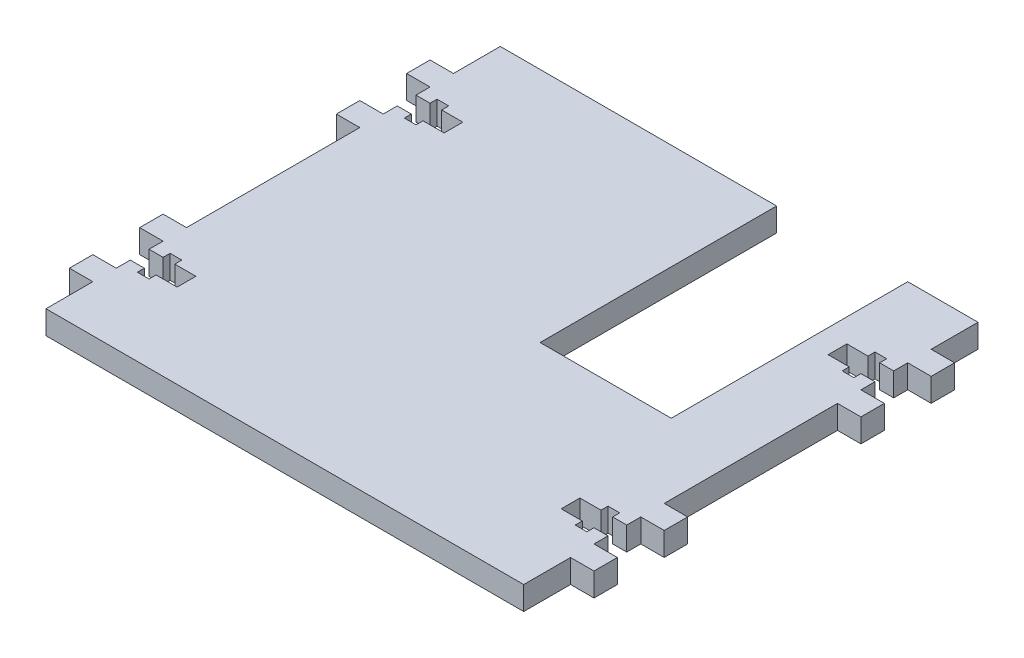
SolidWorks part; units mm, degrees
ref_plane "Front Plane" through (0, 0, 0) normal (0, 0, 1) x (1, 0, 0)
ref_plane "Top Plane" through (0, 0, 0) normal (0, 1, 0) x (1, 0, 0)
ref_plane "Right Plane" through (0, 0, 0) normal (1, 0, 0) x (0, 0, -1)
sketch "Sketch2" plane through (0, 0, 0) normal (0, 1, 0) x (1, 0, 0)
  line L58 (143.4819, 36.3281) -> (143.4819, 33.3281)
  line L59 (41.4819, 51.3281) -> (100.4819, 51.3281)
  line L84 (41.4819, 51.3281) -> (41.4819, 41.3281)
  line L85 (41.4819, -45.6719) -> (143.4819, -45.6719)
  line L86 (143.4819, 51.3281) -> (143.4819, 41.3281)
  line L87 (143.4819, 36.3281) -> (148.4819, 36.3281)
  line L88 (143.4819, 41.3281) -> (148.4819, 41.3281)
  line L89 (148.4819, 36.3281) -> (148.4819, 41.3281)
  line L90 (143.4819, 26.3281) -> (148.4819, 26.3281)
  line L91 (143.4819, 21.3281) -> (148.4819, 21.3281)
  line L92 (148.4819, 26.3281) -> (148.4819, 21.3281)
  line L93 (143.4819, 21.3281) -> (143.4819, -15.6719)
  line L94 (92.4819, 51.3281) -> (92.4819, -45.6719) construction
  line L95 (41.4819, 2.8281) -> (143.4819, 2.8281) construction
  line L96 (41.4819, 21.3281) -> (36.4819, 21.3281)
  line L97 (36.4819, 26.3281) -> (36.4819, 21.3281)
  line L98 (41.4819, 26.3281) -> (36.4819, 26.3281)
  line L99 (36.4819, 36.3281) -> (36.4819, 41.3281)
  line L100 (41.4819, 36.3281) -> (36.4819, 36.3281)
  line L101 (41.4819, 41.3281) -> (36.4819, 41.3281)
  line L102 (148.4819, -30.6719) -> (148.4819, -35.6719)
  line L103 (143.4819, -35.6719) -> (148.4819, -35.6719)
  line L104 (143.4819, -30.6719) -> (148.4819, -30.6719)
  line L105 (148.4819, -20.6719) -> (148.4819, -15.6719)
  line L106 (143.4819, -15.6719) -> (148.4819, -15.6719)
  line L107 (143.4819, -20.6719) -> (148.4819, -20.6719)
  line L108 (41.4819, -35.6719) -> (36.4819, -35.6719)
  line L109 (41.4819, -30.6719) -> (36.4819, -30.6719)
  line L110 (41.4819, -15.6719) -> (36.4819, -15.6719)
  line L111 (41.4819, -20.6719) -> (36.4819, -20.6719)
  line L112 (36.4819, -30.6719) -> (36.4819, -35.6719)
  line L113 (36.4819, -20.6719) -> (36.4819, -15.6719)
  line L114 (143.4819, -20.6719) -> (143.4819, -23.6719)
  line L115 (143.4819, -35.6719) -> (143.4819, -45.6719)
  line L116 (41.4819, -35.6719) -> (41.4819, -45.6719)
  line L117 (41.4819, -20.6719) -> (41.4819, -23.6719)
  line L118 (41.4819, 21.3281) -> (41.4819, -15.6719)
  line L119 (41.4819, 36.3281) -> (41.4819, 33.3281)
  line L120 (143.4819, 31.3281) -> (41.4819, 31.3281) construction
  line L121 (143.4819, 33.3281) -> (140.4819, 33.3281)
  line L122 (143.4819, 29.3281) -> (140.4819, 29.3281)
  line L123 (133.4819, 33.3281) -> (133.4819, 29.3281)
  line L124 (140.4819, 33.3281) -> (140.4819, 34.8281)
  line L125 (140.4819, 34.8281) -> (137.9819, 34.8281)
  line L126 (137.9819, 33.3281) -> (137.9819, 34.8281)
  line L127 (137.9819, 33.3281) -> (133.4819, 33.3281)
  line L128 (140.4819, 29.3281) -> (140.4819, 27.8281)
  line L129 (140.4819, 27.8281) -> (137.9819, 27.8281)
  line L130 (137.9819, 29.3281) -> (137.9819, 27.8281)
  line L131 (137.9819, 29.3281) -> (133.4819, 29.3281)
  line L132 (143.4819, 29.3281) -> (143.4819, 26.3281)
  line L133 (44.4819, 33.3281) -> (44.4819, 34.8281)
  line L134 (46.9819, 33.3281) -> (46.9819, 34.8281)
  line L135 (44.4819, 34.8281) -> (46.9819, 34.8281)
  line L136 (41.4819, 33.3281) -> (44.4819, 33.3281)
  line L137 (41.4819, 29.3281) -> (44.4819, 29.3281)
  line L138 (44.4819, 29.3281) -> (44.4819, 27.8281)
  line L139 (46.9819, 29.3281) -> (46.9819, 27.8281)
  line L140 (44.4819, 27.8281) -> (46.9819, 27.8281)
  line L141 (46.9819, 29.3281) -> (51.4819, 29.3281)
  line L142 (51.4819, 33.3281) -> (51.4819, 29.3281)
  line L143 (46.9819, 33.3281) -> (51.4819, 33.3281)
  line L144 (41.4819, -27.6719) -> (44.4819, -27.6719)
  line L145 (44.4819, -27.6719) -> (44.4819, -29.1719)
  line L146 (46.9819, -27.6719) -> (46.9819, -29.1719)
  line L147 (44.4819, -29.1719) -> (46.9819, -29.1719)
  line L148 (46.9819, -27.6719) -> (51.4819, -27.6719)
  line L149 (51.4819, -27.6719) -> (51.4819, -23.6719)
  line L150 (46.9819, -23.6719) -> (51.4819, -23.6719)
  line L151 (46.9819, -23.6719) -> (46.9819, -22.1719)
  line L152 (44.4819, -23.6719) -> (44.4819, -22.1719)
  line L153 (44.4819, -22.1719) -> (46.9819, -22.1719)
  line L154 (41.4819, -23.6719) -> (44.4819, -23.6719)
  line L155 (137.9819, -27.6719) -> (137.9819, -29.1719)
  line L156 (140.4819, -29.1719) -> (137.9819, -29.1719)
  line L157 (140.4819, -27.6719) -> (140.4819, -29.1719)
  line L158 (143.4819, -27.6719) -> (140.4819, -27.6719)
  line L159 (143.4819, -23.6719) -> (140.4819, -23.6719)
  line L160 (140.4819, -23.6719) -> (140.4819, -22.1719)
  line L161 (140.4819, -22.1719) -> (137.9819, -22.1719)
  line L162 (137.9819, -23.6719) -> (137.9819, -22.1719)
  line L163 (137.9819, -23.6719) -> (133.4819, -23.6719)
  line L164 (133.4819, -27.6719) -> (133.4819, -23.6719)
  line L165 (137.9819, -27.6719) -> (133.4819, -27.6719)
  line L166 (41.4819, 29.3281) -> (41.4819, 26.3281)
  line L167 (41.4819, -27.6719) -> (41.4819, -30.6719)
  line L168 (143.4819, -27.6719) -> (143.4819, -30.6719)
  line L169 (128.4819, 51.3281) -> (143.4819, 51.3281)
  line L171 (100.4819, 51.3281) -> (100.4819, 0.8281)
  line L172 (100.4819, 0.8281) -> (128.4819, 0.8281)
  line L173 (128.4819, 51.3281) -> (128.4819, 0.8281)
  dimension "D1" = 102
  dimension "D2" = 97
  dimension "D3" = 5
  dimension "D4" = 10
  dimension "D5" = 10
  dimension "D6" = 3
  dimension "D7" = 10
  dimension "D8" = 3
  dimension "D9" = 2.5
  dimension "D10" = 15
  dimension "D11" = 28
  dimension "D12" = 50.5
  dimension "D14" = 1.5
extrude "Boss-Extrude2" add sketch "Sketch2" along normal blind 5
